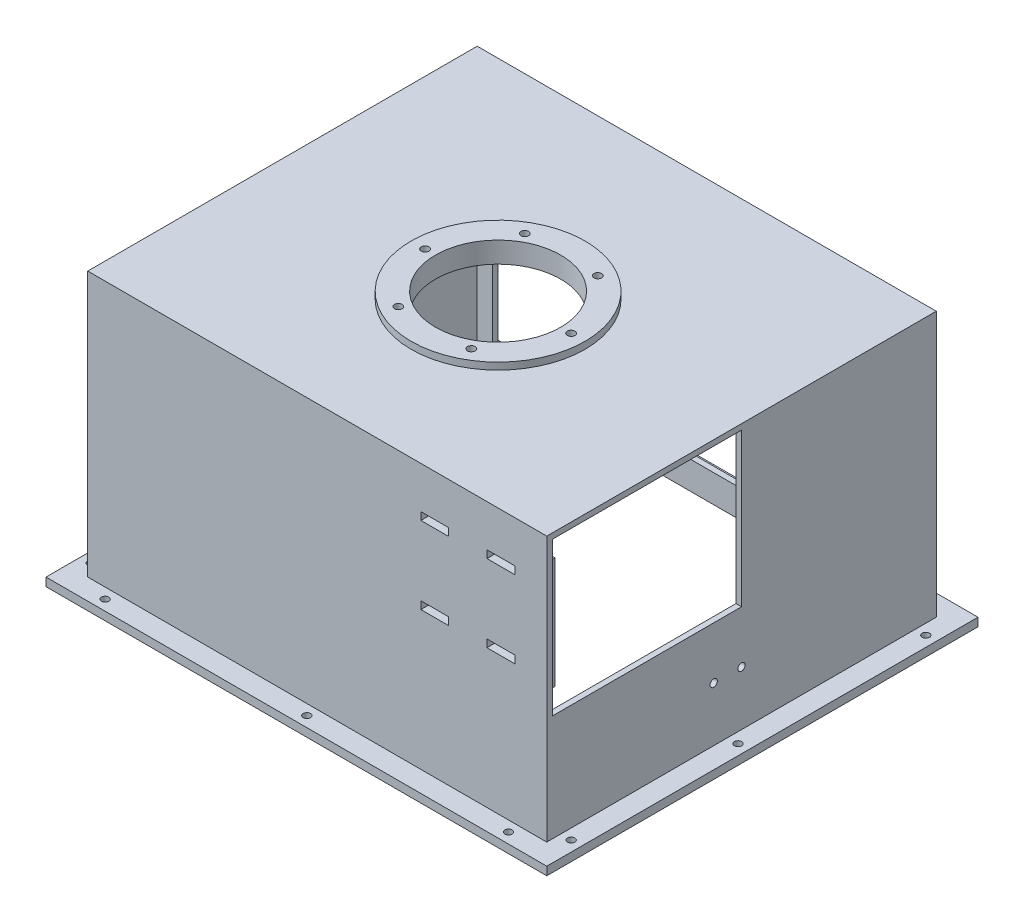
SolidWorks part; units mm, degrees
ref_plane "Piano frontale" through (0, 0, 0) normal (0, 0, 1) x (1, 0, 0)
ref_plane "Piano superiore" through (0, 0, 0) normal (0, 1, 0) x (1, 0, 0)
ref_plane "Piano destro" through (0, 0, 0) normal (1, 0, 0) x (0, 0, -1)
sketch "Schizzo1" plane through (0, 0, 0) normal (0, 1, 0) x (1, 0, 0)
  line L1 (0, 0) -> (720, 0)
  line L2 (0, 0) -> (0, 620)
  line L3 (0, 620) -> (720, 620)
  line L4 (720, 0) -> (720, 620)
  dimension "D1" = 720
  dimension "D2" = 620
extrude "Estrusione-Estrusione1" add sketch "Schizzo1" along normal blind 393
sketch "Schizzo3" plane through (0, 393, 0) normal (0, 1, 0) x (1, 0, 0)
  line L1 (30, 30) -> (690, 30)
  line L2 (0, 0) -> (30, 0)
  line L3 (0, 0) -> (720, 0) construction
  line L4 (30, 0) -> (30, 30) construction
  line L5 (30, 30) -> (30, 590)
  line L6 (30, 590) -> (690, 590)
  line L7 (690, 30) -> (690, 590)
  line L8 (0, 0) -> (720, 0)
  line L9 (0, 0) -> (0, 620)
  line L10 (0, 620) -> (720, 620)
  line L11 (720, 0) -> (720, 620)
  dimension "D1" = 30
  dimension "D2" = 30
  dimension "D3" = 660
  dimension "D4" = 560
extrude "Taglio-Estrusione1" cut sketch "Schizzo3" against normal blind 381
sketch "Schizzo4" plane through (0, 12, 0) normal (0, 1, 0) x (1, 0, 0)
  line L0 (360, 0) -> (360, 620) construction
  line L1 (0, 0) -> (720, 0) construction
  line L2 (720, 620) -> (0, 620) construction
  line L3 (0, 310) -> (720, 310) construction
  line L4 (360, 605) -> (650, 605) construction
  line L5 (705, 605) -> (705, 560) construction
  line L6 (0, 620) -> (0, 0) construction
  line L7 (720, 0) -> (720, 620) construction
  line L8 (360, 620) -> (360, 590) construction
  line L9 (30, 590) -> (690, 590) construction
  line L10 (360, 605) -> (705, 605) construction
  line L11 (705, 560) -> (705, 290) construction
  line L12 (705, 290) -> (705, 50) construction
  circle A0 centre (360, 605) radius 5.25
  circle A1 centre (650, 605) radius 5.25
  circle A2 centre (70, 605) radius 5.25
  circle A3 centre (650, 15) radius 5.25
  circle A4 centre (360, 15) radius 5.25
  circle A5 centre (70, 15) radius 5.25
  circle A6 centre (705, 560) radius 5.25
  circle A7 centre (705, 290) radius 5.25
  circle A8 centre (705, 50) radius 5.25
  circle A9 centre (15, 50) radius 5.25
  circle A10 centre (15, 290) radius 5.25
  circle A11 centre (15, 560) radius 5.25
  dimension "D2" = 10.5
  dimension "D4" = 10.5
  dimension "D9" = 10.5
  dimension "D10" = 10.5
  dimension "D11" = 10.5
  dimension "D1" = 345
  dimension "D3" = 290
  dimension "D5" = 295
  dimension "D6" = 45
  dimension "D7" = 270
  dimension "D8" = 240
extrude "Taglio-Estrusione2" cut sketch "Schizzo4" against normal up to surface (12 mm away) up to face at (360, 0, -310)
sketch "Schizzo5" plane through (0, 0, 0) normal (0, 1, 0) x (1, 0, 0)
  line L0 (0, 620) -> (38, 620) construction
  line L1 (720, 620) -> (0, 620) construction
  line L2 (38, 620) -> (38, 582) construction
  line L4 (38, 582) -> (682, 582)
  line L5 (38, 582) -> (38, 38)
  line L6 (38, 38) -> (682, 38)
  line L7 (682, 582) -> (682, 38)
  dimension "D1" = 38
  dimension "D2" = 38
  dimension "D3" = 644
  dimension "D4" = 544
extrude "Taglio-Estrusione3" cut sketch "Schizzo5" along normal blind 385
sketch "Schizzo6" plane through (0, 393, 0) normal (0, 1, 0) x (1, 0, 0)
  line L0 (15, 290) -> (705, 290) construction
  circle A2 centre (360, 290) radius 125
  dimension "D1" = 250
extrude "Estrusione-Estrusione2" add sketch "Schizzo6" along normal blind 10 and the other way blind 20
sketch "Schizzo7" plane through (0, 403, 0) normal (0, 1, 0) x (1, 0, 0)
  line L0 (15, 290) -> (705, 290) construction
  circle A0 centre (360, 290) radius 90
  dimension "D1" = 180
extrude "Taglio-Estrusione4" cut sketch "Schizzo7" against normal up to surface (30 mm away) up to face at (360, 373, -165)
hole_wizard "Foro per Vite M10-1" positions "Schizzo3D1" profile "Schizzo12" hole size "M10" standard "ISO"
sketch3d "Schizzo3D1"
  line L0 (360, 403, -290) -> (465, 403, -290) construction
  line L1 (360, 373, -290) -> (360, 403, -290) construction
  line L2 (360, 393, -290) -> (360, 403, -290) construction
  point P0 (465, 403, -290)
  dimension "D1" = 105
sketch "Schizzo12" plane through (465, 403, -290) normal (1, 0, 0) x (0, 0, 1)
  line L0 (0, 0) -> (0, 33.3037)
  line L1 (0, 33.3037) -> (5.5, 29.999)
  line L2 (5.5, 29.999) -> (5.5, 0)
  line L5 (5.5, 0) -> (0, 0)
  line L10 (0, 33.3037) -> (-5.5, 29.999) construction
  line L11 (0, -6.35) -> (0, 107.95) construction
  dimension "Hole Dia." = 11
  dimension "Hole Depth" = 29.999
  dimension "Drill Angle" = 118
pattern_circular "RipetizioneCircolare1" count 6 over 360 about axis through (360, 0, -290) along (0, 1, 0) of "Foro per Vite M10-1"
sketch "Schizzo14" plane through (0, 0, -582) normal (0, 0, 1) x (1, 0, 0)
  line L0 (0, 0) -> (0, 40) construction
  line L1 (0, 40) -> (60, 40) construction
  line L3 (60, 40) -> (660, 40)
  line L4 (60, 40) -> (60, 340)
  line L5 (60, 340) -> (660, 340)
  line L6 (660, 40) -> (660, 340)
  dimension "D1" = 40
  dimension "D2" = 60
  dimension "D3" = 600
  dimension "D4" = 300
extrude "Taglio-Estrusione5" cut sketch "Schizzo14" against normal up to surface (8 mm away) up to face at (360, 202.5, -590)
sketch "Schizzo16" plane through (30, 0, 0) normal (-1, 0, 0) x (0, 0, 1)
  line L0 (-620, 0) -> (-620, 90) construction
  line L1 (-620, 90) -> (-310, 90) construction
  line L2 (-310, 90) -> (-270, 90) construction
  circle A0 centre (-310, 90) radius 5.25
  circle A1 centre (-270, 90) radius 5.25
  dimension "D4" = 10.5
  dimension "D5" = 10.5
  dimension "D1" = 90
  dimension "D2" = 310
  dimension "D3" = 40
extrude "Taglio-Estrusione6" cut sketch "Schizzo16" against normal up to surface (8 mm away) up to face at (38, 192.5, -310)
sketch "Schizzo17" plane through (690, 0, 0) normal (1, 0, 0) x (0, 0, -1)
  line L0 (620, 0) -> (620, 90) construction
  line L1 (620, 90) -> (310, 90) construction
  line L2 (310, 90) -> (270, 90) construction
  circle A0 centre (310, 90) radius 5.25
  circle A1 centre (270, 90) radius 5.25
  dimension "D4" = 10.5
  dimension "D5" = 10.5
  dimension "D1" = 90
  dimension "D2" = 310
  dimension "D3" = 40
extrude "Taglio-Estrusione7" cut sketch "Schizzo17" against normal up to surface (8 mm away) up to face at (682, 192.5, -310)
sketch "Schizzo18" plane through (682, 0, 0) normal (-1, 0, 0) x (0, 0, 1)
  line L1 (-38, 385) -> (-310, 385)
  line L2 (-38, 385) -> (-38, 165)
  line L3 (-38, 165) -> (-310, 165)
  line L4 (-310, 385) -> (-310, 165)
  dimension "D1" = 220
  dimension "D2" = 272
extrude "Taglio-Estrusione8" cut sketch "Schizzo18" against normal up to surface (8 mm away) up to face at (690, 90, -315.25)
sketch "Schizzo19" plane through (0, 0, -38) normal (0, 0, -1) x (-1, 0, 0)
  line L0 (-682, 0) -> (-682, 192) construction
  line L1 (-682, 385) -> (-682, 165) construction
  line L3 (-682, 192) -> (-482, 192)
  line L4 (-682, 192) -> (-682, 352)
  line L5 (-682, 352) -> (-482, 352)
  line L6 (-482, 192) -> (-482, 352)
  dimension "D1" = 192
  dimension "D2" = 200
  dimension "D3" = 160
extrude "Estrusione-Estrusione3" add sketch "Schizzo19" along normal blind 12
sketch "Schizzo20" plane through (0, 0, -50) normal (0, 0, -1) x (-1, 0, 0)
  line L0 (-690, 272) -> (-624, 272) construction
  line L1 (-644, 222) -> (-604, 222)
  line L2 (-690, 385) -> (-690, 165) construction
  line L3 (-624, 272) -> (-529, 272) construction
  line L4 (-682, 0) -> (-682, 216.5) construction
  line L5 (-682, 352) -> (-682, 192) construction
  line L6 (-682, 216.5) -> (-624, 216.5) construction
  line L7 (-624, 216.5) -> (-529, 216.5) construction
  line L8 (-624, 216.5) -> (-624, 222) construction
  line L9 (-644, 222) -> (-644, 211)
  line L10 (-644, 211) -> (-604, 211)
  line L11 (-604, 211) -> (-604, 222)
  line L12 (-529, 216.5) -> (-529, 222) construction
  line L13 (-549, 222) -> (-509, 222)
  line L14 (-549, 222) -> (-549, 211)
  line L15 (-549, 211) -> (-509, 211)
  line L16 (-509, 211) -> (-509, 222)
  line L17 (-549, 322) -> (-509, 322)
  line L18 (-509, 333) -> (-509, 322)
  line L19 (-549, 333) -> (-509, 333)
  line L20 (-549, 322) -> (-549, 333)
  line L21 (-644, 322) -> (-644, 333)
  line L22 (-644, 333) -> (-604, 333)
  line L23 (-604, 333) -> (-604, 322)
  line L24 (-644, 322) -> (-604, 322)
  point P15 (-624, 222)
  point P21 (-529, 222)
  dimension "D1" = 272
  dimension "D2" = 5.5
  dimension "D3" = 216.5
  dimension "D4" = 95
  dimension "D5" = 58
  dimension "D6" = 40
  dimension "D7" = 11
  dimension "D8" = 40
  dimension "D9" = 11
  dimension "D10" = 5.5
extrude "Taglio-Estrusione9" cut sketch "Schizzo20" against normal up to surface (20 mm away) up to face at (360, 202.5, -30)
